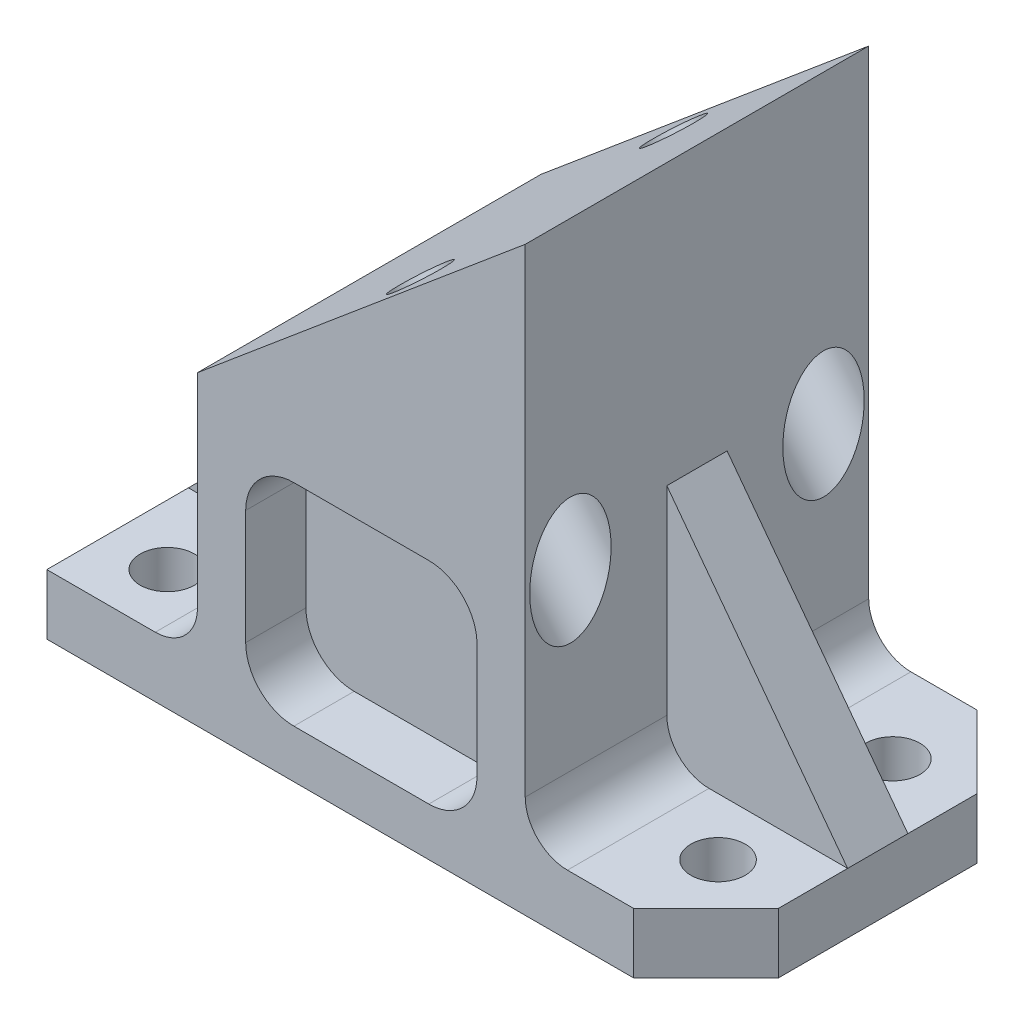
SolidWorks part; units mm, degrees
material "ABS"
ref_plane "Front Plane" through (0, 0, 0) normal (0, 0, 1) x (1, 0, 0)
ref_plane "Top Plane" through (0, 0, 0) normal (0, 1, 0) x (1, 0, 0)
ref_plane "Right Plane" through (0, 0, 0) normal (1, 0, 0) x (0, 0, -1)
sketch "Sketch2" plane through (0, 0, 0) normal (0, 0, 1) x (1, 0, 0)
  line L0 (0, 0) -> (54.3892, 45.6379)
  line L1 (54.3892, 45.6379) -> (54.3892, -50.8)
  line L2 (54.3892, -50.8) -> (0, -50.8)
  line L3 (0, -50.8) -> (0, 0)
  dimension "D1" = 71
  dimension "D2" = 50.8
  dimension "D3" = 40
extrude "Boss-Extrude1" add sketch "Sketch2" along normal blind 57
sketch "Sketch3" plane through (0, 0, 0) normal (-0.6428, 0.766, 0) x (0.766, 0.6428, 0)
  line L0 (71, -57) -> (71, 0) construction
  line L1 (71, -57) -> (0, -57) construction
  line L2 (71, 0) -> (0, 0) construction
  circle A0 centre (38.5, -7.5) radius 4
  circle A1 centre (38.5, -49.5) radius 4
  dimension "D4" = 8
  dimension "D1" = 32.5
  dimension "D2" = 7.5
  dimension "D3" = 7.5
extrude "Cut-Extrude1" cut sketch "Sketch3" against normal through all
sketch "Sketch4" plane through (54.3892, 0, 0) normal (1, 0, 0) x (0, 0, -1)
  line L0 (-49.5, 1.2998) -> (-7.0648, 1.2998) construction
  ellipse E0 centre (-49.5, -4.9231) end of major axis (-49.5, 1.2998) minor radius 4 construction
ref_plane "Plane1" through (32.1394, -38.3022, 0) normal (-0.6428, 0.766, 0) x (0.766, 0.6428, 0)
sketch "Sketch5" plane through (32.1394, -38.3022, 0) normal (-0.6428, 0.766, 0) x (0.766, 0.6428, 0)
  circle A0 centre (38.5, -49.5) radius 4 construction
  circle A1 centre (38.5, -7.5) radius 4 construction
  circle A2 centre (38.5, -49.5) radius 4
  circle A3 centre (38.5, -7.5) radius 4
  point P0 (38.5, -49.5)
  point P2 (38.5, -7.5)
hole_wizard "CBORE for M8 SHCS2" positions "Sketch5" profile "Sketch6" counterbore size "M8" standard "ANSI Metric" end condition through all
sketch "Sketch6" plane through (61.6321, -13.5549, 49.5) normal (0, 0, 1) x (0.766, 0.6428, 0)
  line L0 (0, 0) -> (0, 84.9607)
  line L1 (0, 84.9607) -> (4.5, 84.9607)
  line L3 (4.5, 84.9607) -> (4.5, 20)
  line L4 (4.5, 20) -> (6.75, 20)
  line L5 (6.75, 20) -> (6.75, 0)
  line L7 (6.75, 0) -> (0, 0)
  line L11 (0, -6.35) -> (0, 107.95) construction
  dimension "Thru Hole Dia." = 9
  dimension "Thru Hole Depth" = 84.9607
  dimension "C'Bore Dia." = 13.5
  dimension "C'Bore Depth" = 20
ref_plane "Plane2" through (20, 0, 0) normal (1, 0, 0) x (0, 0, -1)
sketch "Sketch7" plane through (0, -50.8, 0) normal (0, -1, 0) x (1, 0, 0)
  line L1 (54.3892, 57) -> (84.3892, 57)
  line L2 (54.3892, 57) -> (54.3892, 0)
  line L3 (54.3892, 0) -> (84.3892, 0)
  line L4 (84.3892, 57) -> (84.3892, 0)
  dimension "D1" = 30
extrude "Boss-Extrude2" add sketch "Sketch7" against normal blind 10
ref_plane "Plane3" through (0, 0, 28.5) normal (0, 0, 1) x (1, 0, 0)
sketch "Sketch8" plane through (0, 0, 28.5) normal (0, 0, 1) x (1, 0, 0)
  line L0 (84.3892, -40.8) -> (54.3892, -0.8)
  line L1 (54.3892, -40.8) -> (54.3892, 45.6379) construction
  line L2 (54.3892, -0.8) -> (54.3892, -40.8)
  line L3 (54.3892, -40.8) -> (84.3892, -40.8)
  dimension "D1" = 40
extrude "Boss-Extrude3" add sketch "Sketch8" along normal blind 5 and the other way blind 5
sketch "Sketch9" plane through (0, -50.8, 0) normal (0, -1, 0) x (1, 0, 0)
  line L0 (0, 0) -> (84.3892, 0) construction
  line L1 (0, 57) -> (-25, 57)
  line L2 (0, 57) -> (0, 0)
  line L3 (0, 0) -> (-25, 0)
  line L4 (-25, 57) -> (-25, 0)
  dimension "D1" = 25
extrude "Boss-Extrude4" add sketch "Sketch9" against normal blind 10
sketch "Sketch10" plane through (0, 0, 28.5) normal (0, 0, 1) x (1, 0, 0)
  line L0 (-25, -40.8) -> (0, -15.8)
  line L1 (0, 0) -> (0, -40.8) construction
  line L2 (0, -15.8) -> (0, -40.8)
  line L3 (0, -40.8) -> (-25, -40.8)
  dimension "D1" = 25
extrude "Boss-Extrude5" add sketch "Sketch10" along normal blind 5 and the other way blind 5
sketch "Sketch11" plane through (0, 0, 0) normal (0, 0, -1) x (-1, 0, 0)
  line L8 (-38.3892, -7.8) -> (-16, -7.8)
  line L16 (-8, -42.8) -> (-8, -3.7305)
  line L17 (-8, -3.7305) -> (-46.3892, 28.4819)
  line L18 (-46.3892, 28.4819) -> (-46.3892, -42.8)
  line L19 (-46.3892, -42.8) -> (-8, -42.8)
  line L20 (-8, -34.8) -> (-8, -15.8)
  line L22 (-46.3892, -15.8) -> (-46.3892, -34.8)
  line L23 (-38.3892, -42.8) -> (-16, -42.8)
  arc A0 (-46.3892, -34.8) -> (-38.3892, -42.8) centre (-38.3892, -34.8) ccw
  arc A1 (-8, -34.8) -> (-16, -42.8) centre (-16, -34.8) cw
  arc A4 (-16, -7.8) -> (-8, -15.8) centre (-16, -15.8) cw
  arc A5 (-38.3892, -7.8) -> (-46.3892, -15.8) centre (-38.3892, -15.8) ccw
  dimension "D2" = 8
  dimension "D4" = 8
  dimension "D3" = 35
  dimension "D1" = 8
extrude "Cut-Extrude2" cut sketch "Sketch11" against normal blind 10
mirror "Mirror1" about plane through (0, 0, 28.5) normal (0, 0, 1) of "Cut-Extrude2"
fillet "Fillet1" radius 7 4 edges at (54.3892, -40.8, 45.25) (54.3892, -40.8, 11.75) (0, -40.8, 45.25) (0, -40.8, 11.75)
chamfer "Chamfer1" distance 12 angle 45 2 edges at (84.3892, -45.8, 57) (84.3892, -45.8, 0)
hole_wizard "M8 Clearance Hole1" positions "Sketch14" profile "Sketch13" hole size "M8" standard "ANSI Metric" end condition through all
sketch "Sketch14" plane through (0, -40.8, 0) normal (0, 1, 0) x (1, 0, 0)
  line L0 (61.3892, 0) -> (72.3892, 0) construction
  line L1 (72.3892, -57) -> (61.3892, -57) construction
  line L2 (-7, -57) -> (-25, -57) construction
  line L3 (-25, 0) -> (-7, 0) construction
  line L4 (-25, -57) -> (-25, -33.5) construction
  point P0 (72.3892, -43)
  point P2 (72.3892, -14)
  point P4 (-15, -10)
  point P6 (-15, -47)
  point P19 (0, 0)
  point P21 (0, 0)
  point P22 (0, 0)
  dimension "D1" = 14
  dimension "D2" = 14
  dimension "D3" = 10
  dimension "D4" = 10
  dimension "D5" = 10
sketch "Sketch13" plane through (72.3892, -40.8, 43) normal (1, 0, 0) x (0, 0, 1)
  line L0 (0, 0) -> (0, 10)
  line L1 (0, 10) -> (4.5, 10)
  line L2 (4.5, 10) -> (4.5, 0)
  line L5 (4.5, 0) -> (0, 0)
  line L11 (0, -6.35) -> (0, 107.95) construction
  dimension "Thru Hole Dia." = 9
  dimension "Thru Hole Depth" = 10
